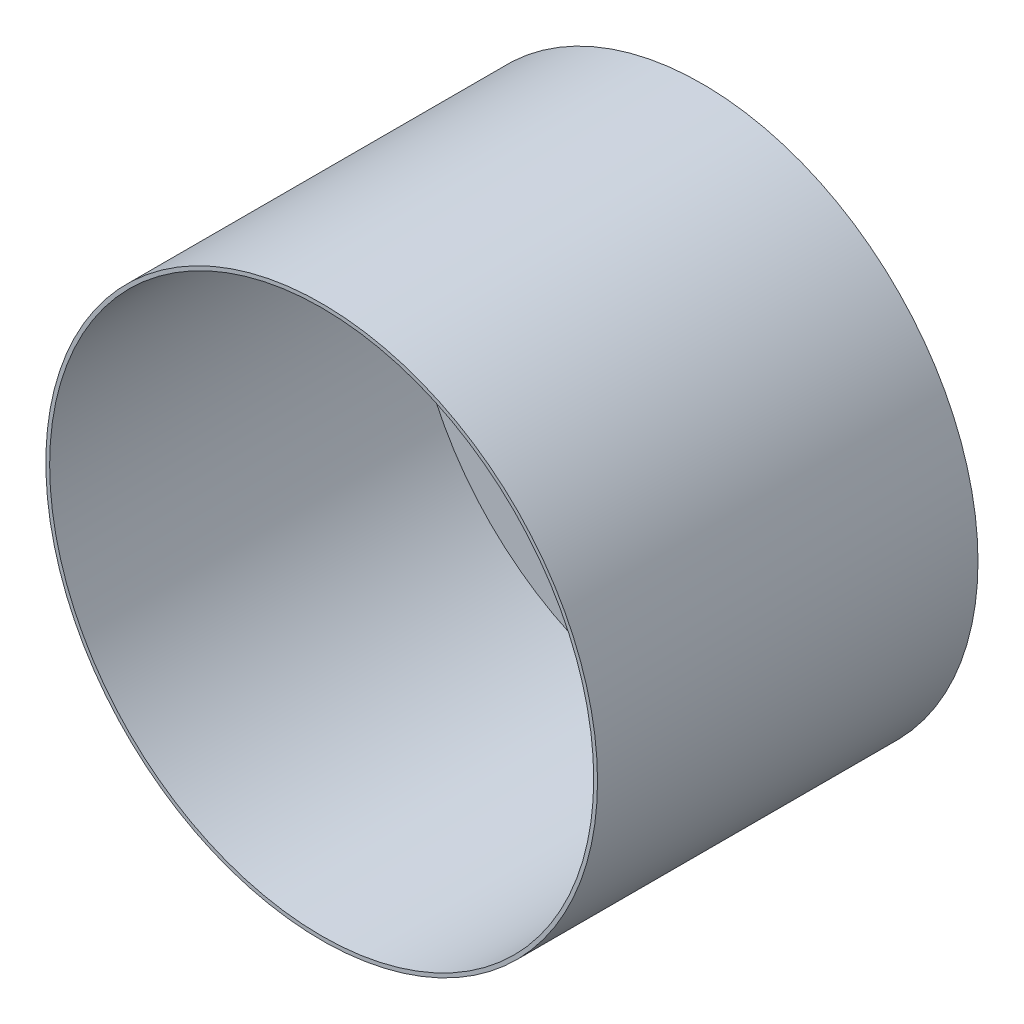
SolidWorks part; units mm, degrees
ref_plane "Front Plane" through (0, 0, 0) normal (0, 0, 1) x (1, 0, 0)
ref_plane "Top Plane" through (0, 0, 0) normal (0, 1, 0) x (1, 0, 0)
ref_plane "Right Plane" through (0, 0, 0) normal (1, 0, 0) x (0, 0, -1)
sketch "Sketch1" plane through (0, 0, 0) normal (0, 0, 1) x (1, 0, 0)
  circle A0 centre (0, 0) radius 7.25
  dimension "D1" = 14.5
extrude "Boss-Extrude1" add sketch "Sketch1" along normal blind 10
sketch "Sketch2" plane through (0, 0, 10) normal (0, 0, 1) x (1, 0, 0)
  circle A2 centre (0, 0) radius 7.15
  circle A3 centre (0, 0) radius 7.15
  dimension "D1" = 0.1
extrude "Cut-Extrude1" cut sketch "Sketch2" against normal blind 9.5
